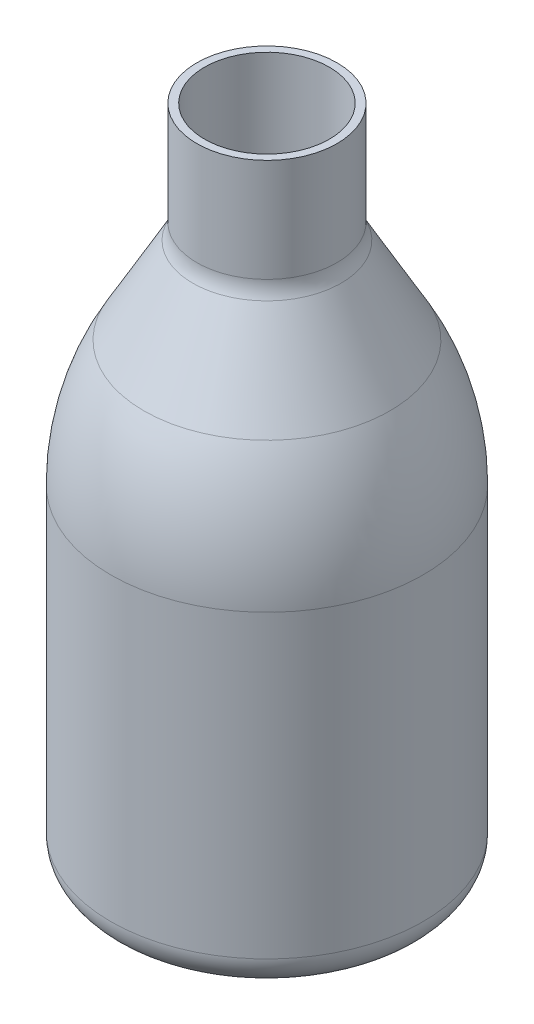
SolidWorks part; units mm, degrees
ref_plane "Front" through (0, 0, 0) normal (0, 0, 1) x (1, 0, 0)
ref_plane "Top" through (0, 0, 0) normal (0, 1, 0) x (1, 0, 0)
ref_plane "Right" through (0, 0, 0) normal (1, 0, 0) x (0, 0, -1)
sketch "Sketch1" plane through (0, 0, 0) normal (0, 0, 1) x (1, 0, 0)
  line L0 (0, 0) -> (0, 132.08)
  line L1 (0, 0) -> (-31.115, 0)
  line L2 (-31.115, 0) -> (-31.115, 79.5745)
  line L3 (-31.115, 79.5745) -> (-13.97, 109.855)
  line L4 (-13.97, 109.855) -> (-13.97, 132.08)
  line L5 (-13.97, 132.08) -> (0, 132.08)
  point P3 (-31.115, 79.5745)
  dimension "D1" = 31.115
  dimension "D2" = 132.08
  dimension "D3" = 22.225
  dimension "D4" = 13.97
  dimension "D5" = 79.5745
revolve "Revolve1" add sketch "Sketch1" angle 360 about L0
fillet "Fillet1" radius 6.35 2 edges at (0, 0, -31.115) (0, 109.855, -13.97)
fillet "Fillet2" radius 50.8 1 edges at (0, 79.5745, -31.115)
shell "Shell1" thickness 1.524
